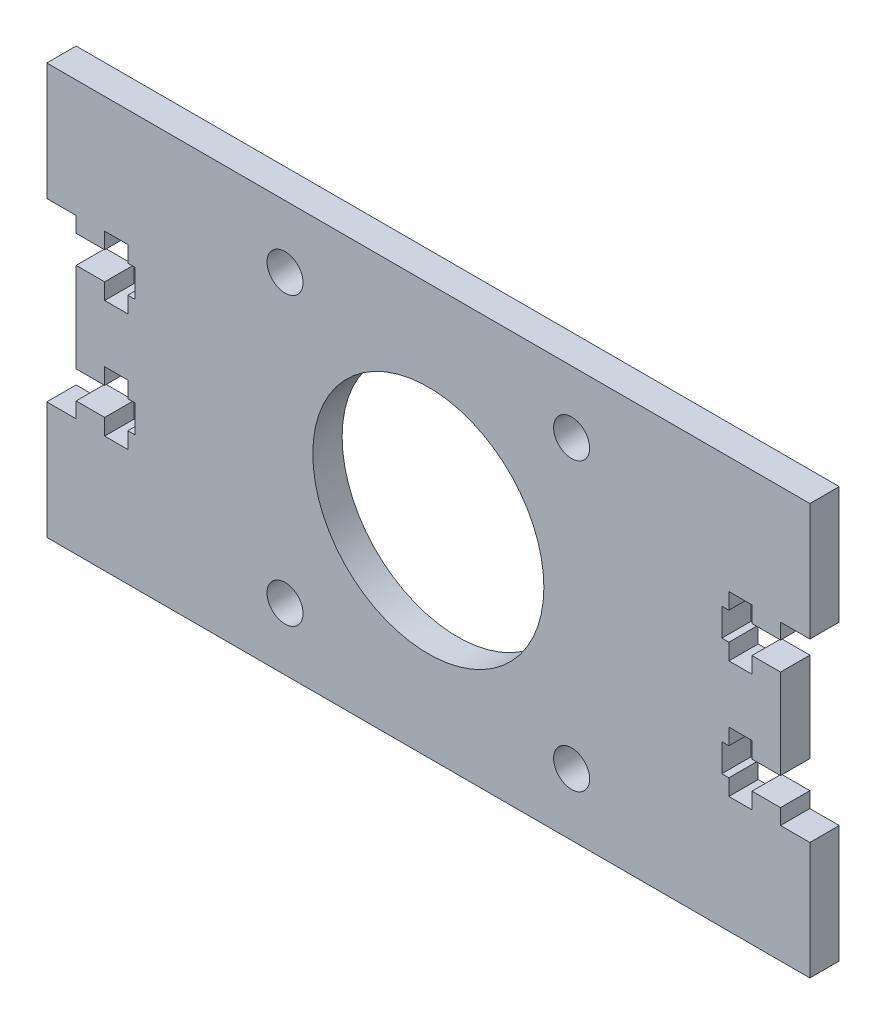
SolidWorks part; units mm, degrees
ref_plane "Front Plane" through (0, 0, 0) normal (0, 0, 1) x (1, 0, 0)
ref_plane "Top Plane" through (0, 0, 0) normal (0, 1, 0) x (1, 0, 0)
ref_plane "Right Plane" through (0, 0, 0) normal (1, 0, 0) x (0, 0, -1)
sketch "Sketch2" plane through (0, 0, 0) normal (0, 0, 1) x (1, 0, 0)
  line L0 (0, 22.225) -> (76.2, 22.225) construction
  line L1 (0, 0) -> (76.2, 0)
  line L2 (0, 12.7) -> (0, 14.375)
  line L3 (0, 44.45) -> (76.2, 44.45)
  line L4 (76.2, 0) -> (76.2, 44.45)
  line L5 (38.1, 44.45) -> (38.1, 0) construction
  line L6 (5.588, 30.075) -> (5.588, 31.825)
  line L7 (0, 0) -> (-3.175, 0)
  line L8 (0, 17.375) -> (0, 31.75)
  line L9 (0, 12.7) -> (-3.175, 12.7)
  line L10 (-3.175, 0) -> (-3.175, 12.7)
  line L11 (0, 17.375) -> (3.088, 17.375)
  line L12 (3.088, 14.375) -> (3.088, 12.625)
  line L13 (0, 14.375) -> (3.088, 14.375)
  line L14 (6.35, 17.375) -> (6.35, 14.375)
  line L15 (73.112, 14.375) -> (73.112, 12.625)
  line L16 (3.088, 19.125) -> (5.588, 19.125)
  line L17 (3.088, 19.125) -> (3.088, 17.375)
  line L18 (3.088, 12.625) -> (5.588, 12.625)
  line L19 (5.588, 19.125) -> (5.588, 17.375)
  line L20 (70.612, 27.075) -> (69.85, 27.075)
  line L21 (5.588, 14.375) -> (5.588, 12.625)
  line L22 (70.612, 30.075) -> (70.612, 31.825)
  line L23 (70.612, 30.075) -> (69.85, 30.075)
  line L24 (5.588, 25.325) -> (5.588, 27.075)
  line L25 (3.088, 31.825) -> (5.588, 31.825)
  line L26 (3.088, 25.325) -> (3.088, 27.075)
  line L27 (3.088, 25.325) -> (5.588, 25.325)
  line L28 (6.35, 27.075) -> (6.35, 30.075)
  line L29 (0, 30.075) -> (3.088, 30.075)
  line L30 (5.588, 17.375) -> (6.35, 17.375)
  line L31 (0, 27.075) -> (3.088, 27.075)
  line L32 (-3.175, 44.45) -> (-3.175, 31.75)
  line L33 (0, 31.75) -> (-3.175, 31.75)
  line L34 (5.588, 30.075) -> (6.35, 30.075)
  line L35 (0, 44.45) -> (-3.175, 44.45)
  line L42 (76.2, 44.45) -> (79.375, 44.45)
  line L43 (5.588, 14.375) -> (6.35, 14.375)
  line L44 (76.2, 31.75) -> (79.375, 31.75)
  line L45 (79.375, 44.45) -> (79.375, 31.75)
  line L46 (76.2, 27.075) -> (73.112, 27.075)
  line L47 (70.612, 14.375) -> (69.85, 14.375)
  line L48 (76.2, 30.075) -> (73.112, 30.075)
  line L49 (69.85, 27.075) -> (69.85, 30.075)
  line L50 (73.112, 25.325) -> (70.612, 25.325)
  line L51 (73.112, 25.325) -> (73.112, 27.075)
  line L52 (73.112, 31.825) -> (70.612, 31.825)
  line L53 (70.612, 25.325) -> (70.612, 27.075)
  line L54 (70.612, 19.125) -> (70.612, 17.375)
  line L55 (73.112, 12.625) -> (70.612, 12.625)
  line L56 (73.112, 19.125) -> (73.112, 17.375)
  line L57 (73.112, 19.125) -> (70.612, 19.125)
  line L58 (69.85, 17.375) -> (69.85, 14.375)
  line L59 (76.2, 14.375) -> (73.112, 14.375)
  line L60 (5.588, 27.075) -> (6.35, 27.075)
  line L61 (76.2, 17.375) -> (73.112, 17.375)
  line L62 (79.375, 0) -> (79.375, 12.7)
  line L63 (76.2, 12.7) -> (79.375, 12.7)
  line L64 (3.088, 30.075) -> (3.088, 31.825)
  line L65 (76.2, 0) -> (79.375, 0)
  line L66 (70.612, 14.375) -> (70.612, 12.625)
  line L67 (70.612, 17.375) -> (69.85, 17.375)
  line L70 (73.112, 30.075) -> (73.112, 31.825)
  circle A0 centre (22.6, 37.725) radius 1.95
  circle A1 centre (53.6, 37.725) radius 1.95
  circle A2 centre (53.6, 6.725) radius 1.95
  circle A3 centre (22.6, 6.725) radius 1.95
  circle A4 centre (38.1, 22.225) radius 12.5
  point P28 (4.338, 15.875)
  point P46 (4.338, 28.575)
  point P73 (71.862, 28.575)
  point P74 (71.862, 15.875)
  dimension "D3" = 3.9
  dimension "D6" = 25
  dimension "D1" = 44.45
  dimension "D2" = 76.2
  dimension "D4" = 31
  dimension "D5" = 31
  dimension "D7" = 3.175
  dimension "D8" = 12.7
  dimension "D9" = 0.762
  dimension "D10" = 2.5
  dimension "D11" = 6.35
  dimension "D12" = 3
  dimension "D13" = 6.5
extrude "Boss-Extrude1" add sketch "Sketch2" along normal blind 3.175 contours L70 L48 L4 L3 L35 L32 L33 L8 L29 L64 L25 L6 L34 L28 L60 L24 L27 L26 L31 L11 L17 L16 L19 L30 L14 L43 L21 L18 L12 L13 L2 L9 L10 L7 L1 L59 L15 L55 L66 L47 L58 L67 L54 L57 L56 L61 | L4 L65 L62 L63 | L45 L42 L4 L44 | A4
